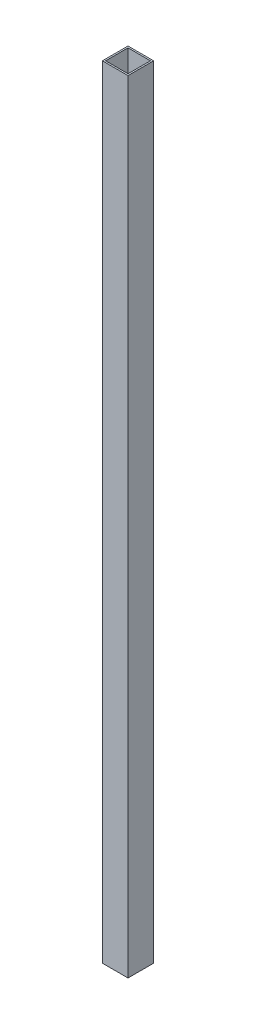
SolidWorks part; units mm, degrees
material "6061 Alloy"
ref_plane "Front Plane" through (0, 0, 0) normal (0, 0, 1) x (1, 0, 0)
ref_plane "Top Plane" through (0, 0, 0) normal (0, 1, 0) x (1, 0, 0)
ref_plane "Right Plane" through (0, 0, 0) normal (1, 0, 0) x (0, 0, -1)
sketch "Sketch1" plane through (0, 0, 0) normal (0, 1, 0) x (1, 0, 0)
  line L1 (-12.7, -12.7) -> (12.7, -12.7)
  line L2 (-12.7, -12.7) -> (-12.7, 12.7)
  line L3 (-12.7, 12.7) -> (12.7, 12.7)
  line L4 (12.7, -12.7) -> (12.7, 12.7)
  line L7 (-11.1125, -11.1125) -> (11.1125, -11.1125)
  line L8 (-11.1125, -11.1125) -> (-11.1125, 11.1125)
  line L9 (-11.1125, 11.1125) -> (11.1125, 11.1125)
  line L10 (11.1125, -11.1125) -> (11.1125, 11.1125)
  point P6 (0, 0)
  dimension "D1" = 25.4
  dimension "D2" = 25.4
  dimension "D3" = 1.5875
  dimension "D4" = 1.5875
  dimension "D5" = 1.5875
extrude "Boss-Extrude1" add sketch "Sketch1" along normal blind 774.7
